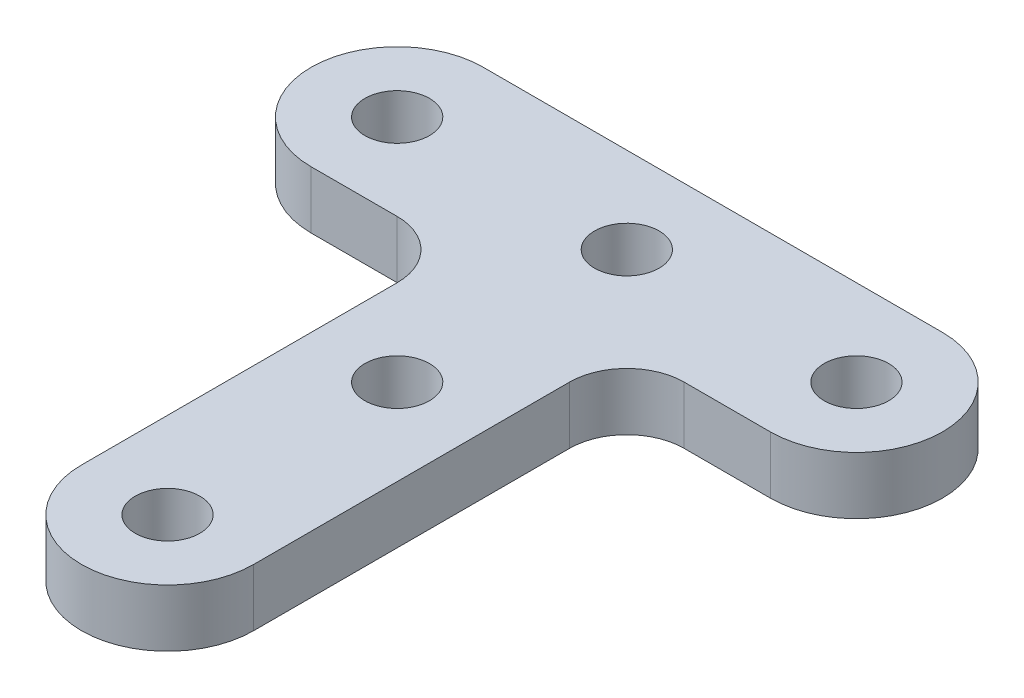
SolidWorks part; units mm, degrees
ref_plane "Front Plane" through (0, 0, 0) normal (0, 0, 1) x (1, 0, 0)
ref_plane "Top Plane" through (0, 0, 0) normal (0, 1, 0) x (1, 0, 0)
ref_plane "Right Plane" through (0, 0, 0) normal (1, 0, 0) x (0, 0, -1)
sketch "Sketch1" plane through (0, 144.9046, 0) normal (0, -1, 0) x (-1, 0, 0)
  line L0 (-24.9619, -1122.1003) -> (-9.0869, -1122.1003) construction
  line L1 (-9.0869, -1122.1003) -> (-9.0869, -1163.3753) construction
  line L2 (9.9631, -1163.3753) -> (9.9631, -1122.1003) construction
  line L3 (9.9631, -1122.1003) -> (25.8381, -1122.1003) construction
  line L4 (-24.9619, -1103.0503) -> (25.8381, -1103.0503) construction
  line L5 (-24.9619, -1122.1003) -> (-9.0869, -1122.1003)
  line L6 (-9.0869, -1122.1003) -> (-9.0869, -1163.3753)
  line L7 (9.9631, -1163.3753) -> (9.9631, -1122.1003)
  line L8 (9.9631, -1122.1003) -> (25.8381, -1122.1003)
  line L9 (-24.9619, -1103.0503) -> (25.8381, -1103.0503)
  circle A0 centre (0.4381, -1163.3753) radius 9.525 construction
  circle A1 centre (25.8381, -1112.5753) radius 9.525 construction
  circle A2 centre (-24.9619, -1112.5753) radius 9.525 construction
  arc A3 (-9.0869, -1163.3753) -> (9.9631, -1163.3753) centre (0.4381, -1163.3753) ccw
  arc A4 (25.8381, -1122.1003) -> (25.8381, -1103.0503) centre (25.8381, -1112.5753) ccw
  arc A5 (-24.9619, -1103.0503) -> (-24.9619, -1122.1003) centre (-24.9619, -1112.5753) ccw
extrude "Boss-Extrude1" add sketch "Sketch1" along normal up to vertex (19.177 mm away) from vertex at 12.827
fillet "Fillet1" radius 6.35 2 edges at (9.0869, 128.9026, 1122.1003) (-9.9631, 128.9026, 1122.1003)
hole_wizard "1/4 Clearance Hole1" positions "Sketch2" profile "Sketch3" hole size "1/4" standard "ANSI Inch" end condition through all
sketch "Sketch2" plane through (0, 125.7276, 0) normal (0, -1, 0) x (-1, 0, 0)
  point P0 (-24.9619, -1112.5753)
  point P4 (25.8381, -1112.5753)
  point P8 (0.4381, -1137.9753)
  point P10 (0.4381, -1163.3753)
  point P12 (0.4381, -1112.5753)
sketch "Sketch3" plane through (24.9619, 125.7276, 1112.5753) normal (1, 0, 0) x (0, 0, -1)
  line L0 (0, 0) -> (0, 6.35)
  line L1 (0, 6.35) -> (3.5712, 6.35)
  line L2 (3.5712, 6.35) -> (3.5712, 0)
  line L5 (3.5712, 0) -> (0, 0)
  line L11 (0, -6.35) -> (0, 107.95) construction
  dimension "Thru Hole Dia." = 7.1425
  dimension "Thru Hole Depth" = 6.35
